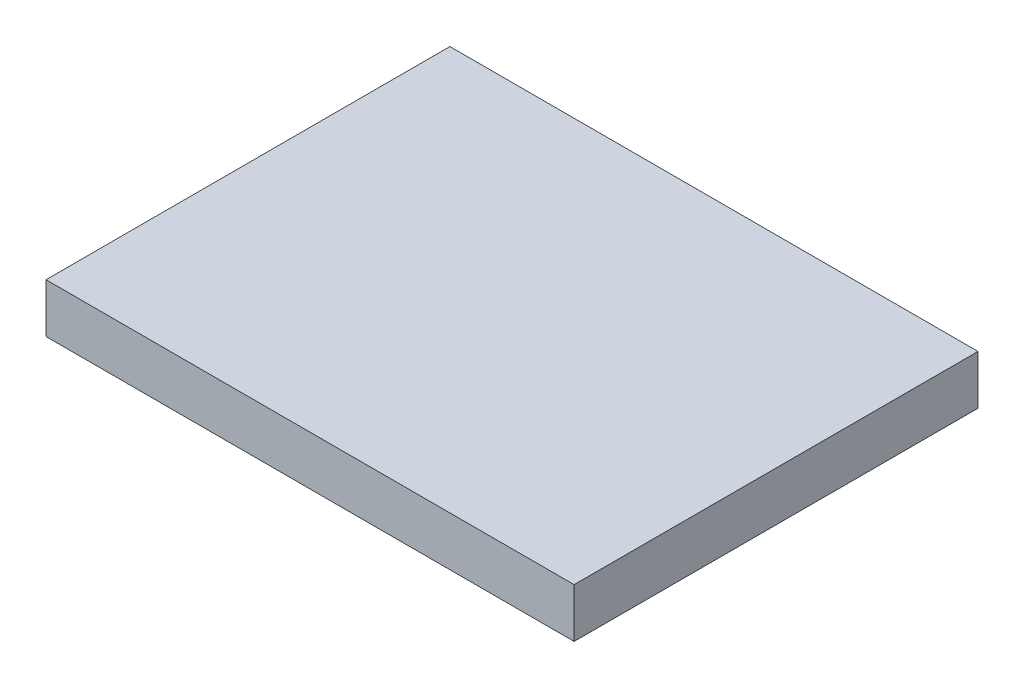
SolidWorks part; units mm, degrees
ref_plane "Front Plane" through (0, 0, 0) normal (0, 0, 1) x (1, 0, 0)
ref_plane "Top Plane" through (0, 0, 0) normal (0, 1, 0) x (1, 0, 0)
ref_plane "Right Plane" through (0, 0, 0) normal (1, 0, 0) x (0, 0, -1)
sketch "Sketch1" plane through (0, 0, 0) normal (0, 1, 0) x (1, 0, 0)
  line L1 (-6.8139, -5.2112) -> (6.8139, -5.2112)
  line L2 (-6.8139, -5.2112) -> (-6.8139, 5.2112)
  line L3 (-6.8139, 5.2112) -> (6.8139, 5.2112)
  line L4 (6.8139, -5.2112) -> (6.8139, 5.2112)
  line L5 (-6.8139, -5.2112) -> (6.8139, 5.2112) construction
  line L6 (-6.8139, 5.2112) -> (6.8139, -5.2112) construction
  point P0 (0, 0)
  point P6 (4.3936, -2.9965)
  point P7 (6.8139, -5.2112)
extrude "Boss-Extrude1" add sketch "Sketch1" along normal blind 1.27
